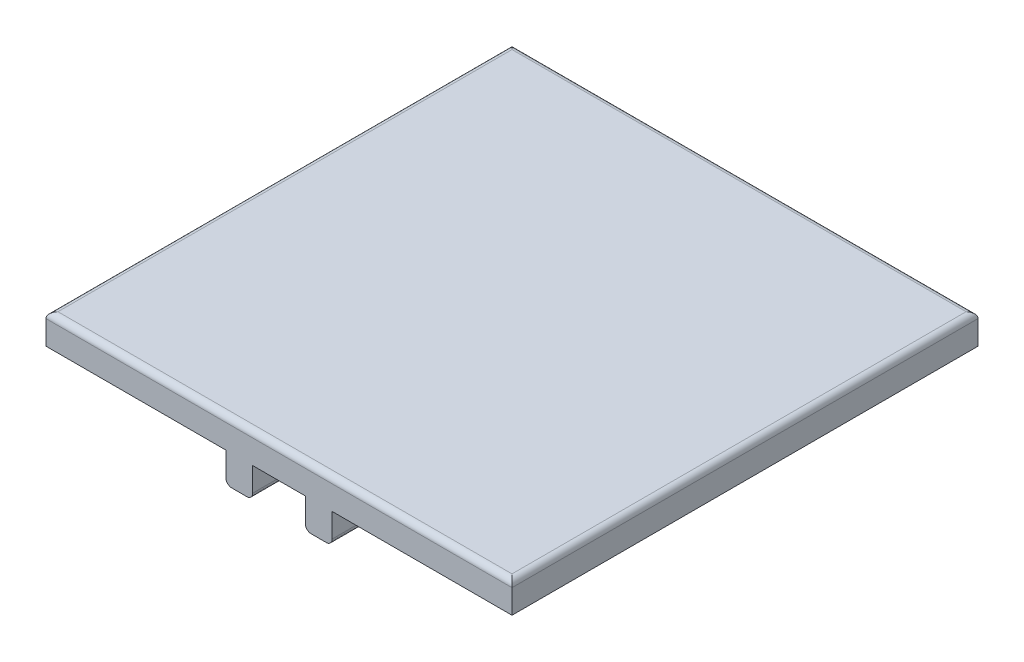
SolidWorks part; units mm, degrees
ref_plane "Front Plane" through (0, 0, 0) normal (0, 0, 1) x (1, 0, 0)
ref_plane "Top Plane" through (0, 0, 0) normal (0, 1, 0) x (1, 0, 0)
ref_plane "Right Plane" through (0, 0, 0) normal (1, 0, 0) x (0, 0, -1)
sketch "Sketch1" plane through (0, 0, 0) normal (0, 0, 1) x (1, 0, 0)
  line L0 (0, 0) -> (0, 35.9328) construction
  line L2 (-39, 2.5) -> (39, 2.5)
  line L3 (-39, 2.5) -> (-39, -2.5)
  line L4 (-39, -2.5) -> (39, -2.5)
  line L5 (39, 2.5) -> (39, -2.5)
  line L6 (-39, 2.5) -> (39, -2.5) construction
  line L7 (-39, -2.5) -> (39, 2.5) construction
  line L8 (-8.9, -2.5) -> (-4.4, -2.5)
  line L9 (-8.9, -2.5) -> (-8.9, -7.5)
  line L10 (-8.9, -7.5) -> (-4.4, -7.5)
  line L11 (-4.4, -2.5) -> (-4.4, -7.5)
  line L12 (4.4, -2.5) -> (8.9, -2.5)
  line L13 (4.4, -2.5) -> (4.4, -7.5)
  line L14 (4.4, -7.5) -> (8.9, -7.5)
  line L15 (8.9, -2.5) -> (8.9, -7.5)
  dimension "D1" = 5
  dimension "D2" = 78
  dimension "D3" = 5
  dimension "D4" = 4.5
  dimension "D5" = 5
  dimension "D6" = 4.5
  dimension "D7" = 8.8
  dimension "D8" = 4.4
extrude "Boss-Extrude2" add sketch "Sketch1" along normal mid plane 78 contours L5 L2 L3 L4 | L11 L4 L9 L10 | L15 L4 L13 L14
fillet "Fillet1" radius 1 8 edges at (-4.4, -7.5, 0) (4.4, -7.5, 0) (8.9, -7.5, 0) (-8.9, -7.5, 0) (39, 2.5, 0) (0, 2.5, -39) (0, 2.5, 39) (-39, 2.5, 0)
